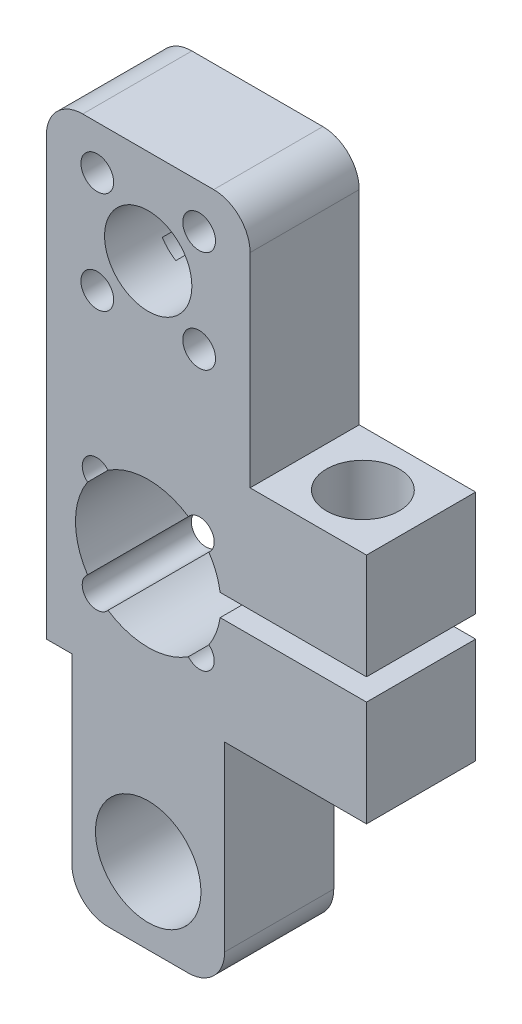
SolidWorks part; units mm, degrees
ref_plane "前视基准面" through (0, 0, 0) normal (0, 0, 1) x (1, 0, 0)
ref_plane "上视基准面" through (0, 0, 0) normal (0, 1, 0) x (1, 0, 0)
ref_plane "右视基准面" through (0, 0, 0) normal (1, 0, 0) x (0, 0, -1)
sketch "草图1" plane through (0, 0, 0) normal (0, 0, 1) x (1, 0, 0)
  line L48 (1164.9408, 1110.9116) -> (1146.9408, 1110.9116)
  line L49 (1141.9408, 1045.9116) -> (1141.9408, 1105.9116)
  line L50 (1166.4408, 1020.9116) -> (1166.4408, 1045.9116)
  line L51 (1169.9408, 1077.9116) -> (1169.9408, 1105.9116)
  line L52 (1185.9408, 1045.9116) -> (1185.9408, 1060.4116)
  line L53 (1185.9408, 1063.4116) -> (1185.9408, 1077.9116)
  line L54 (1177.9408, 1042.5452) -> (1177.9408, 1082.3164) construction
  line L61 (1138.7988, 1061.9116) -> (1196.9975, 1061.9116) construction
  line L62 (1165.8276, 1060.4116) -> (1185.9408, 1060.4116)
  line L63 (1165.8276, 1063.4116) -> (1185.9408, 1063.4116)
  line L64 (1166.4408, 1045.9116) -> (1185.9408, 1045.9116)
  line L65 (1169.9408, 1077.9116) -> (1185.9408, 1077.9116)
  line L66 (1145.4408, 1020.9116) -> (1145.4408, 1045.9116)
  line L67 (1145.4408, 1045.9116) -> (1141.9408, 1045.9116)
  line L68 (1161.4408, 1015.9116) -> (1150.4408, 1015.9116)
  line L91 (1155.9408, 1011.0872) -> (1155.9408, 1116.8995) construction
  line L93 (1144.2858, 1097.9116) -> (1168.0953, 1097.9116) construction
  line L94 (1143.1897, 1090.9116) -> (1154.367, 1090.9116) construction
  line L95 (1148.9408, 1096.3307) -> (1148.9408, 1085.5239) construction
  line L96 (1157.1897, 1090.9116) -> (1168.367, 1090.9116) construction
  line L97 (1162.9408, 1096.3307) -> (1162.9408, 1085.5239) construction
  line L98 (1157.1897, 1104.9116) -> (1168.367, 1104.9116) construction
  line L99 (1162.9408, 1110.3307) -> (1162.9408, 1099.5239) construction
  line L100 (1143.1897, 1104.9116) -> (1154.367, 1104.9116) construction
  line L101 (1148.9408, 1110.3307) -> (1148.9408, 1099.5239) construction
  arc A4 (1169.9408, 1105.9116) -> (1164.9408, 1110.9116) centre (1164.9408, 1105.9116) ccw
  arc A5 (1146.9408, 1110.9116) -> (1141.9408, 1105.9116) centre (1146.9408, 1105.9116) ccw
  arc A6 (1164.2775, 1056.3891) -> (1165.8276, 1060.4116) centre (1155.9408, 1061.9116) ccw
  arc A7 (1150.4182, 1053.5749) -> (1161.4633, 1053.5749) centre (1155.9408, 1061.9116) ccw
  arc A8 (1147.604, 1067.4342) -> (1147.604, 1056.3891) centre (1155.9408, 1061.9116) ccw
  arc A9 (1161.4633, 1070.2484) -> (1150.4182, 1070.2484) centre (1155.9408, 1061.9116) ccw
  arc A10 (1165.8276, 1063.4116) -> (1164.2775, 1067.4342) centre (1155.9408, 1061.9116) ccw
  circle A11 centre (1162.9408, 1104.9116) radius 2.25
  circle A13 centre (1155.9408, 1097.9116) radius 6
  circle A14 centre (1148.9408, 1104.9116) radius 2.25
  circle A16 centre (1148.9408, 1090.9116) radius 2.25
  circle A18 centre (1162.9408, 1090.9116) radius 2.25
  arc A20 (1145.4408, 1020.9116) -> (1150.4408, 1015.9116) centre (1150.4408, 1020.9116) ccw
  arc A21 (1161.4408, 1015.9116) -> (1166.4408, 1020.9116) centre (1161.4408, 1020.9116) ccw
  arc A22 (1164.2775, 1067.4342) -> (1161.4633, 1070.2484) centre (1163.0118, 1068.9827) ccw
  arc A23 (1150.4182, 1070.2484) -> (1147.604, 1067.4342) centre (1148.8697, 1068.9827) ccw
  arc A24 (1161.4633, 1053.5749) -> (1164.2775, 1056.3891) centre (1163.0118, 1054.8406) ccw
  arc A25 (1147.604, 1056.3891) -> (1150.4182, 1053.5749) centre (1148.8697, 1054.8406) ccw
  circle A28 centre (1155.9408, 1026.4116) radius 7.25
extrude "拉伸1" add sketch "草图1" along normal blind 15
sketch "草图2" plane through (0, 0, 0) normal (0, 0, -1) x (-1, 0, 0)
  circle A0 centre (-1148.9408, 1090.9116) radius 4.25
  circle A1 centre (-1162.9408, 1090.9116) radius 4.25
  circle A2 centre (-1148.9408, 1104.9116) radius 4.25
  circle A3 centre (-1162.9408, 1104.9116) radius 4.25
  dimension "D1" = 8.5
extrude "拉伸2" cut sketch "草图2" against normal blind 8
sketch "草图3" plane through (0, 1077.9116, 0) normal (0, 1, 0) x (1, 0, 0)
  line L0 (1185.9408, 0) -> (1169.9408, 0) construction
  line L1 (1169.9408, -15) -> (1169.9408, 0) construction
  circle A0 centre (1177.9408, -7.5) radius 3.4
  point P2 (1177.9408, 0)
  dimension "D2" = 8
  dimension "D3" = 6.8
  dimension "D1" = 7.5
extrude "拉伸3" cut sketch "草图3" against normal through all
sketch "草图4" plane through (0, 1077.9116, 0) normal (0, 1, 0) x (1, 0, 0)
  circle A0 centre (1177.9408, -7.5) radius 5
  dimension "D1" = 10
extrude "拉伸4" cut sketch "草图4" against normal blind 15
